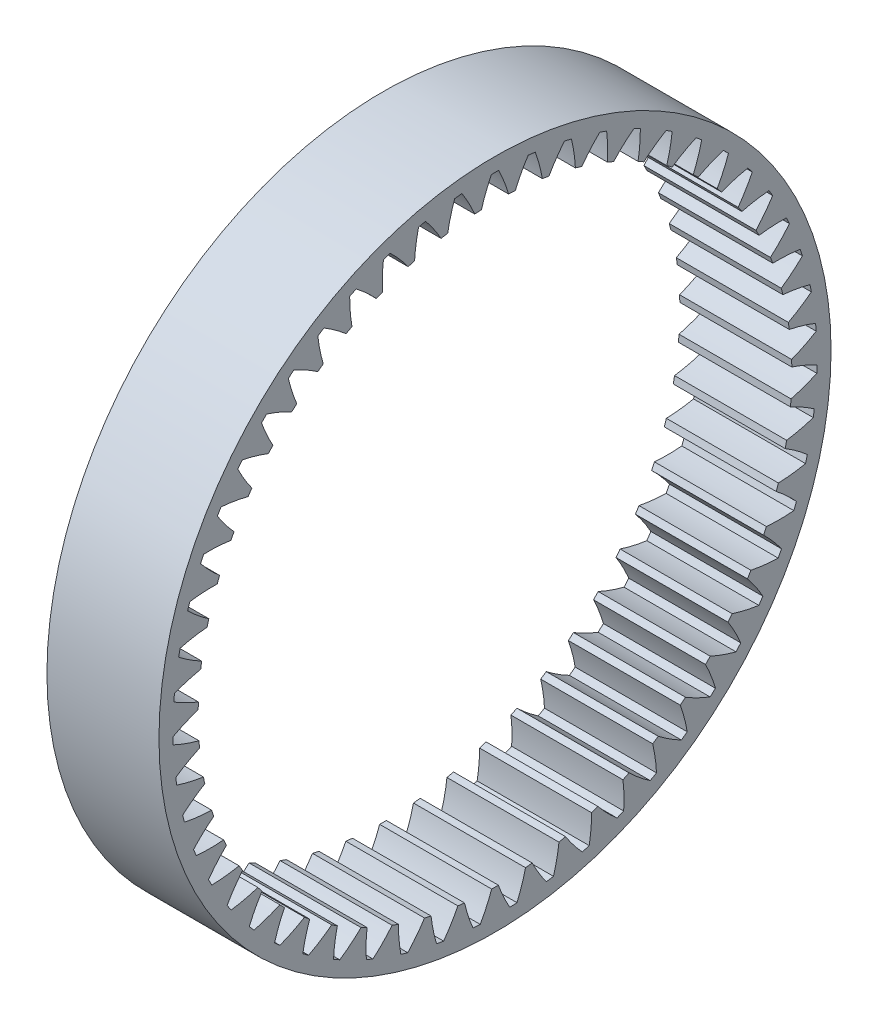
SolidWorks part; units mm, degrees
ref_plane "Plane1" through (0, 0, 0) normal (0, 0, 1) x (1, 0, 0)
ref_plane "Plane2" through (0, 0, 0) normal (0, 1, 0) x (1, 0, 0)
ref_plane "Plane3" through (0, 0, 0) normal (1, 0, 0) x (0, 0, -1)
sketch "HoldingSke" plane through (0, 0, 0) normal (0, 1, 0) x (1, 0, 0)
  line L0 (0, 0) -> (0.3824, -0.5461)
  line L1 (-15, 0) -> (100, 0) construction
  line L2 (0, 0) -> (-2.1039, 2.3779)
  line L3 (0, 0) -> (-11.863, 4.5341)
  line L4 (0, 0) -> (4.9534, 7.0742)
  line L5 (0, 0) -> (-23.7986, -8.8762)
  line L6 (0, 0) -> (-10.5278, -7.1032)
  line L7 (-2.1039, 2.3779) -> (3.3635, 27.1825)
  line L8 (-76.2, 3.8779) -> (-54.61, 3.8779)
  line L9 (-71.009, 38.7566) -> (-53.1078, 45.2721)
  line L10 (-76.2, 71.12) -> (104.1128, 71.12)
  line L11 (0, 0) -> (-15, 0)
  line L12 (-76.2, 101.6) -> (-76.147, 101.6)
  line L13 (24.9733, 27.94) -> (52.9518, 28.4284)
  line L14 (24.9733, 27.94) -> (24.9743, 27.94)
  line L15 (24.9733, 27.94) -> (100.4006, 29.5858)
  circle A0 centre (0, 0) radius 45
  circle A1 centre (0, 0) radius 12.7
  circle A2 centre (0, 0) radius 12.7
  dimension "MHD" = 25.4
  dimension "Hub_dia" = 25.4
  dimension "Diameter" = 90
  dimension "Num_teeth" = 55
  dimension "Pitch" = 0.6667
  dimension "Overall_len" = 25.4
  dimension "Show_teeth" = 55
  dimension "Thickness" = 12.7
  dimension "OAL" = 25.4001
  dimension "T_dim" = 21.59
  dimension "Ap" = 20
  dimension "H" = 19.05
  dimension "Pitch_radius" = 180.3128
  dimension "Width" = 15
  dimension "Backlash" = 0.053
  dimension "Addendum_fac" = 1
  dimension "Dedendum_fac" = 1.25
  dimension "Clearance_fac" = 0.25
  dimension "Dedendum_add" = 0.001
  dimension "Module" = 1.5
sketch "BasProSke" plane through (0, 0, 0) normal (0, 1, 0) x (1, 0, 0)
  line L0 (-10, 0) -> (60, 0) construction
  line L1 (0, 39.75) -> (0, 45)
  line L2 (0, 39.75) -> (15, 39.75)
  line L3 (15, 39.75) -> (15, 45)
  line L4 (15, 45) -> (0, 45)
  dimension "Diameter" = 90
  dimension "Thickness" = 15
  dimension "Inside_diameter" = 79.5
revolve "Base-Revolve" add sketch "BasProSke" angle 360 about L0
sketch "TooCutSke" plane through (0, 0, 0) normal (1, 0, 0) x (0, 0, -1)
  line L3 (1.3104, 41.2292) -> (1.3104, 53.6633) construction
  line L4 (0, 0) -> (0, 59.563) construction
  line L5 (0, 0) -> (-3.9007, 68.2161) construction
  line L6 (-17.9742, 33.9153) -> (35.7895, 36.9896) construction
  circle A0 centre (0, 0) radius 41.25 construction
  circle A1 centre (0, 0) radius 43.126 construction
  circle A2 centre (0, 0) radius 34.8861 construction
  circle A3 centre (0, 0) radius 39.7246 construction
  arc A4 (1.8281, 39.6825) -> (0.4812, 43.1233) centre (-17.9742, 33.9153) ccw
  arc A5 (1.8281, 39.6825) -> (-1.8281, 39.6825) centre (0, 0) ccw
  arc A6 (0.4812, 43.1233) -> (-0.4812, 43.1233) centre (0, 0) ccw
  arc A7 (-0.4812, 43.1233) -> (-1.8281, 39.6825) centre (17.9742, 33.9153) ccw
  dimension "Pitch_dia" = 82.5
  dimension "Base_dia" = 69.7722
  dimension "Root_dia" = 86.252
  dimension "Overcut_dia" = 79.4492
  dimension "Flank_rad" = 20.625
  dimension "Half_ang" = 3.273
  dimension "Half_CT" = 1.3104
extrude "ToothCut" cut sketch "TooCutSke" along normal through all
fillet "Breaks" [suppressed] radius 0.15
fillet "RootFillets" [suppressed] radius 0.376
pattern_circular "TeethCuts" count 55 every 6.545 about axis through (-10, 0, 0) along (1, 0, 0) of "RootFillets", "Breaks", "ToothCut"
equation "' \"Module@HoldingSke\" = 6.35"
equation "' \"Num_teeth@HoldingSke\" = 24"
equation "' \"Ap@HoldingSke\" =  14.5"
equation "' \"Ap@HoldingSke\" = 14.5"
equation "' \"Width@HoldingSke\" = 12"
equation "' \"Diameter@HoldingSke\" = 8 * 25.4"
equation "' \"Show_teeth@HoldingSke\" = 100"
equation "' \"Backlash@HoldingSke\" = 0.009 * 25.4"
equation "' \"Addendum_fac@HoldingSke\" = 1.0"
equation "' \"Dedendum_fac@HoldingSke\" = 1.25"
equation "' \"Dedendum_add@HoldingSke\" = 0.00005 * 25.4"
equation "' \"Clearance_fac@HoldingSke\" = 0.25"
equation "\"Pitch@HoldingSke\" = 1 / \"Module@HoldingSke\" "
equation "\"Overcut_dia@TooCutSke\" = (\"Num_teeth@HoldingSke\" - 2 * \"Addendum_fac@HoldingSke\") / \"Pitch@HoldingSke\" - 0.002 * 25.4"
equation "\"Pitch_dia@TooCutSke\" = \"Num_teeth@HoldingSke\" / \"Pitch@HoldingSke\""
equation "\"Base_dia@TooCutSke\" = \"Num_teeth@HoldingSke\" / \"Pitch@HoldingSke\" * cos((\"Ap@HoldingSke\"  * 3.14159265 / 180)) * 0.90"
equation "\"Root_dia@TooCutSke\" = \"Num_teeth@HoldingSke\"  / \"Pitch@HoldingSke\" + 2 *  \"Dedendum_fac@HoldingSke\"/ \"Pitch@HoldingSke\" + \"Dedendum_add@HoldingSke\" * 2"
equation "\"Half_ang@TooCutSke\" = 180 / \"Num_teeth@HoldingSke\""
equation "\"Half_CT@TooCutSke\" = \"Num_teeth@HoldingSke\" / \"Pitch@HoldingSke\" * sin((3.14159265 / 2 / \"Num_teeth@HoldingSke\")) / 2 + 10 * \"Backlash@HoldingSke\" / 4"
equation "\"Flank_rad@TooCutSke\" = \"Num_teeth@HoldingSke\" / \"Pitch@HoldingSke\" / 4"
equation "\"Radius@RootFillets\"= \"Clearance_fac@HoldingSke\" / \"Pitch@HoldingSke\" + \"Dedendum_add@HoldingSke\""
equation "\"Break_rad@Breaks\" = 0.02 / \"Pitch@HoldingSke\" * 5"
equation "\"Num_teeth@TeethCuts\" = int( \"Show_teeth@HoldingSke\" ) + 1"
equation "\"Num_teeth@TeethCuts\" = ((sgn( \"Num_teeth@TeethCuts\" - \"Num_teeth@HoldingSke\" )-1)*( \"Num_teeth@TeethCuts\" - \"Num_teeth@HoldingSke\" ))/-2+ \"Num_teeth@HoldingSke\""
equation "\"Num_teeth@TeethCuts\" = ((sgn( \"Num_teeth@TeethCuts\" - 2.0)+1)*( \"Num_teeth@TeethCuts\" - 2.0))/2 +2.0"
equation "\"Angle@TeethCuts\" = 360.0 / \"Num_teeth@HoldingSke\""
equation "\"Diameter@BasProSke\" = \"Num_teeth@HoldingSke\"  / \"Pitch@HoldingSke\" + 2 *  \"Dedendum_fac@HoldingSke\"/ \"Pitch@HoldingSke\" + \"Dedendum_add@HoldingSke\" * 2 + 0.002 * 25.4"
equation "\"Diameter@BasProSke\" = ((sgn( \"Diameter@BasProSke\"  - \"Diameter@HoldingSke\" )+1)*( \"Diameter@BasProSke\"  - \"Diameter@HoldingSke\" ))/2 + \"Diameter@HoldingSke\""
equation "\"Inside_diameter@BasProSke\" =  (\"Num_teeth@HoldingSke\" - 2 * \"Addendum_fac@HoldingSke\") / \"Pitch@HoldingSke\" "
equation "\"Thickness@BasProSke\"  = \"Width@HoldingSke\""
